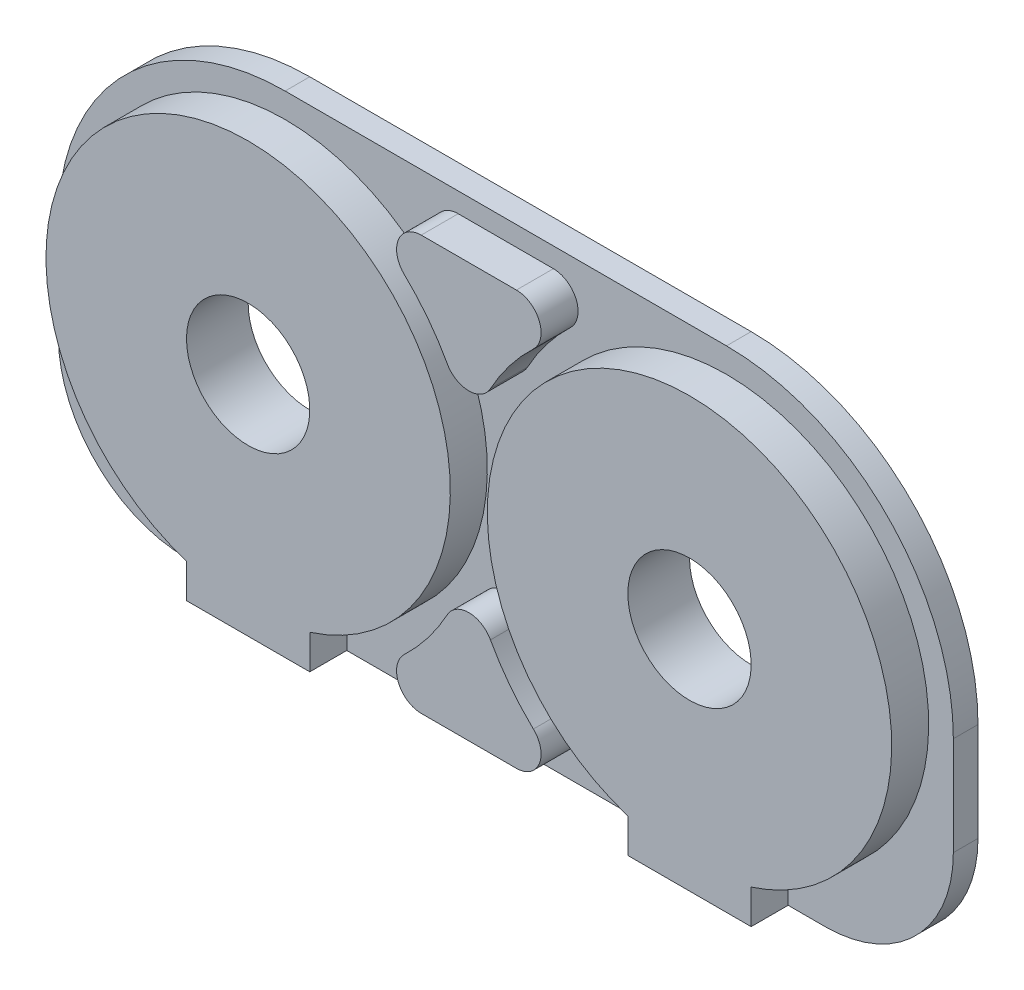
SolidWorks part; units mm, degrees
ref_plane "Спереди" through (0, 0, 0) normal (0, 0, 1) x (1, 0, 0)
ref_plane "Сверху" through (0, 0, 0) normal (0, 1, 0) x (1, 0, 0)
ref_plane "Справа" through (0, 0, 0) normal (1, 0, 0) x (0, 0, -1)
sketch "Эскиз2" plane through (0, 0, 0) normal (0, 0, 1) x (1, 0, 0)
  line L0 (1.93, 8.6) -> (-1.93, 8.6) construction
  line L1 (-1.93, -8.4) -> (1.93, -8.4)
  line L2 (-1.93, -8.4) -> (1.93, -8.4)
  line L3 (1.93, 8.4) -> (-1.93, 8.4)
  line L4 (1.93, 8.4) -> (-1.93, 8.4)
  line L5 (-1.93, -8.6) -> (1.93, -8.6) construction
  line L6 (-11.45, -8.0194) -> (-11.45, -7.8096)
  line L7 (-6.45, -8.0194) -> (-6.45, -7.8096)
  line L8 (6.45, -8.0194) -> (6.45, -7.8096)
  line L9 (11.45, -8.0194) -> (11.45, -7.8096)
  line L10 (-6.45, -8.0194) -> (-6.45, -9.2) construction
  line L11 (-6.45, -9.2) -> (-11.45, -9.2) construction
  line L12 (-11.45, -9.2) -> (-11.45, -8.0194) construction
  line L13 (11.45, -9.2) -> (6.45, -9.2) construction
  line L14 (6.45, -9.2) -> (6.45, -8.0194) construction
  line L15 (11.45, -8.0194) -> (11.45, -9.2) construction
  line L16 (-6.45, -8.0194) -> (-6.45, -9.2)
  line L17 (-6.45, -9.2) -> (-11.45, -9.2)
  line L18 (-11.45, -9.2) -> (-11.45, -8.0194)
  line L19 (11.45, -9.2) -> (6.45, -9.2)
  line L20 (6.45, -9.2) -> (6.45, -8.0194)
  line L21 (11.45, -8.0194) -> (11.45, -9.2)
  circle A0 centre (-8.95, 0) radius 8.4 construction
  circle A1 centre (8.95, 0) radius 8.4 construction
  circle A2 centre (-8.95, 0) radius 8.4 construction
  circle A3 centre (8.95, 0) radius 8.4 construction
  arc A4 (11.45, -7.8096) -> (6.45, -7.8096) centre (8.95, 0) ccw
  arc A5 (-6.45, -7.8096) -> (-11.45, -7.8096) centre (-8.95, 0) ccw
  arc A6 (-11.45, -7.8096) -> (-6.45, -7.8096) centre (-8.95, 0) ccw construction
  arc A7 (-1.93, 8.6) -> (-2.7559, 6.5294) centre (-1.93, 7.4) ccw construction
  arc A8 (-1.0529, 4.317) -> (-2.7559, 6.5294) centre (-8.95, 0) ccw construction
  arc A9 (-1.0529, 4.317) -> (1.0529, 4.317) centre (0, 4.8926) ccw construction
  arc A10 (2.7559, 6.5294) -> (1.0529, 4.317) centre (8.95, 0) ccw construction
  arc A11 (2.7559, 6.5294) -> (1.93, 8.6) centre (1.93, 7.4) ccw construction
  arc A12 (-1.93, 8.4) -> (-2.6183, 6.6745) centre (-1.93, 7.4) ccw
  arc A13 (-2.6183, -6.6745) -> (-1.93, -8.4) centre (-1.93, -7.4) ccw
  arc A14 (1.93, -8.4) -> (2.6183, -6.6745) centre (1.93, -7.4) ccw
  arc A15 (0.8775, -4.4129) -> (2.6183, -6.6745) centre (8.95, 0) ccw
  arc A16 (0.8775, -4.4129) -> (-0.8775, -4.4129) centre (0, -4.8926) ccw
  arc A17 (-2.6183, -6.6745) -> (-0.8775, -4.4129) centre (-8.95, 0) ccw
  arc A18 (-2.6183, -6.6745) -> (-1.93, -8.4) centre (-1.93, -7.4) ccw
  arc A19 (1.93, -8.4) -> (2.6183, -6.6745) centre (1.93, -7.4) ccw
  arc A20 (0.8775, -4.4129) -> (2.6183, -6.6745) centre (8.95, 0) ccw
  arc A21 (0.8775, -4.4129) -> (-0.8775, -4.4129) centre (0, -4.8926) ccw
  arc A22 (-2.6183, -6.6745) -> (-0.8775, -4.4129) centre (-8.95, 0) ccw
  arc A23 (-0.8775, 4.4129) -> (-2.6183, 6.6745) centre (-8.95, 0) ccw
  arc A24 (-0.8775, 4.4129) -> (0.8775, 4.4129) centre (0, 4.8926) ccw
  arc A25 (2.6183, 6.6745) -> (0.8775, 4.4129) centre (8.95, 0) ccw
  arc A26 (2.6183, 6.6745) -> (1.93, 8.4) centre (1.93, 7.4) ccw
  arc A27 (-1.93, 8.4) -> (-2.6183, 6.6745) centre (-1.93, 7.4) ccw
  arc A28 (-0.8775, 4.4129) -> (-2.6183, 6.6745) centre (-8.95, 0) ccw
  arc A29 (-0.8775, 4.4129) -> (0.8775, 4.4129) centre (0, 4.8926) ccw
  arc A30 (2.6183, 6.6745) -> (0.8775, 4.4129) centre (8.95, 0) ccw
  arc A31 (2.6183, 6.6745) -> (1.93, 8.4) centre (1.93, 7.4) ccw
  arc A32 (-2.7559, -6.5294) -> (-1.93, -8.6) centre (-1.93, -7.4) ccw construction
  arc A33 (1.93, -8.6) -> (2.7559, -6.5294) centre (1.93, -7.4) ccw construction
  arc A34 (1.0529, -4.317) -> (2.7559, -6.5294) centre (8.95, 0) ccw construction
  arc A35 (1.0529, -4.317) -> (-1.0529, -4.317) centre (0, -4.8926) ccw construction
  arc A36 (-2.7559, -6.5294) -> (-1.0529, -4.317) centre (-8.95, 0) ccw construction
  circle A37 centre (-8.95, 0) radius 8.2 construction
  arc A38 (6.45, -7.8096) -> (11.45, -7.8096) centre (8.95, 0) ccw construction
  circle A39 centre (8.95, 0) radius 8.2 construction
  arc A57 (-11.45, -8.0194) -> (-6.45, -8.0194) centre (-8.95, 0) ccw construction
  arc A58 (6.45, -8.0194) -> (11.45, -8.0194) centre (8.95, 0) ccw construction
  arc A59 (-11.45, -8.0194) -> (-6.45, -8.0194) centre (-8.95, 0) ccw construction
  arc A60 (6.45, -8.0194) -> (11.45, -8.0194) centre (8.95, 0) ccw construction
  dimension "D1" = 0.2
  dimension "D2" = 0
  dimension "D3" = 0
  dimension "D4" = 0.2
extrude "Бобышка-Вытянуть1" add sketch "Эскиз2" along normal blind 1.5
sketch "Эскиз3" plane through (0, 0, 0) normal (0, 0, -1) x (-1, 0, 0)
  line L0 (-8.95, 9.2) -> (8.95, 9.2) construction
  line L1 (-8.95, 9.2) -> (8.95, 9.2)
  line L2 (18.15, 0) -> (18.15, -4) construction
  line L4 (-18.15, -4) -> (-18.15, 0) construction
  line L5 (18.15, 0) -> (18.15, -4)
  line L7 (-18.15, -4) -> (-18.15, 0)
  line L8 (12.95, -9.2) -> (11.45, -9.2) construction
  line L9 (6.45, -9.2) -> (11.45, -9.2) construction
  line L10 (6.45, -9.2) -> (-6.45, -9.2) construction
  line L11 (-11.45, -9.2) -> (-6.45, -9.2) construction
  line L12 (-11.45, -9.2) -> (-12.95, -9.2) construction
  line L13 (12.95, -9.2) -> (11.45, -9.2)
  line L14 (6.45, -9.2) -> (11.45, -9.2)
  line L15 (6.45, -9.2) -> (-6.45, -9.2)
  line L16 (-11.45, -9.2) -> (-6.45, -9.2)
  line L17 (-11.45, -9.2) -> (-12.95, -9.2)
  arc A0 (18.15, 0) -> (8.95, 9.2) centre (8.95, 0) ccw construction
  arc A1 (12.95, -9.2) -> (18.15, -4) centre (12.95, -4) ccw construction
  arc A3 (-8.95, 9.2) -> (-18.15, 0) centre (-8.95, 0) ccw construction
  arc A4 (18.15, 0) -> (8.95, 9.2) centre (8.95, 0) ccw
  arc A5 (12.95, -9.2) -> (18.15, -4) centre (12.95, -4) ccw
  arc A7 (-8.95, 9.2) -> (-18.15, 0) centre (-8.95, 0) ccw
  arc A8 (-18.15, -4) -> (-12.95, -9.2) centre (-12.95, -4) ccw construction
  arc A9 (-18.15, -4) -> (-12.95, -9.2) centre (-12.95, -4) ccw
extrude "Бобышка-Вытянуть2" add sketch "Эскиз3" along normal blind 1
sketch "Эскиз4" plane through (0, 0, -1) normal (0, 0, -1) x (-1, 0, 0)
  line L4 (-18.15, 0) -> (-18.15, -4)
  line L5 (-12.95, -9.2) -> (12.95, -9.2)
  line L6 (18.15, -4) -> (18.15, 0)
  line L7 (8.95, 9.2) -> (-8.95, 9.2)
  line L8 (-18.15, 0) -> (-18.15, -4)
  line L9 (-12.95, -9.2) -> (12.95, -9.2)
  line L10 (18.15, -4) -> (18.15, 0)
  line L11 (8.95, 9.2) -> (-8.95, 9.2)
  circle A0 centre (8.95, 0) radius 2.5 construction
  circle A1 centre (8.95, 0) radius 2.5
  circle A2 centre (-8.95, 0) radius 2.5 construction
  circle A3 centre (-8.95, 0) radius 2.5
  arc A4 (-8.95, 9.2) -> (-18.15, 0) centre (-8.95, 0) ccw
  arc A5 (-18.15, -4) -> (-12.95, -9.2) centre (-12.95, -4) ccw
  arc A6 (12.95, -9.2) -> (18.15, -4) centre (12.95, -4) ccw
  arc A7 (18.15, 0) -> (8.95, 9.2) centre (8.95, 0) ccw
  arc A8 (-8.95, 9.2) -> (-18.15, 0) centre (-8.95, 0) ccw
  arc A9 (-18.15, -4) -> (-12.95, -9.2) centre (-12.95, -4) ccw
  arc A10 (12.95, -9.2) -> (18.15, -4) centre (12.95, -4) ccw
  arc A11 (18.15, 0) -> (8.95, 9.2) centre (8.95, 0) ccw
  dimension "D1" = 0
extrude "Вырез-Вытянуть1" cut sketch "Эскиз4" against normal through all contours A3 | A1
